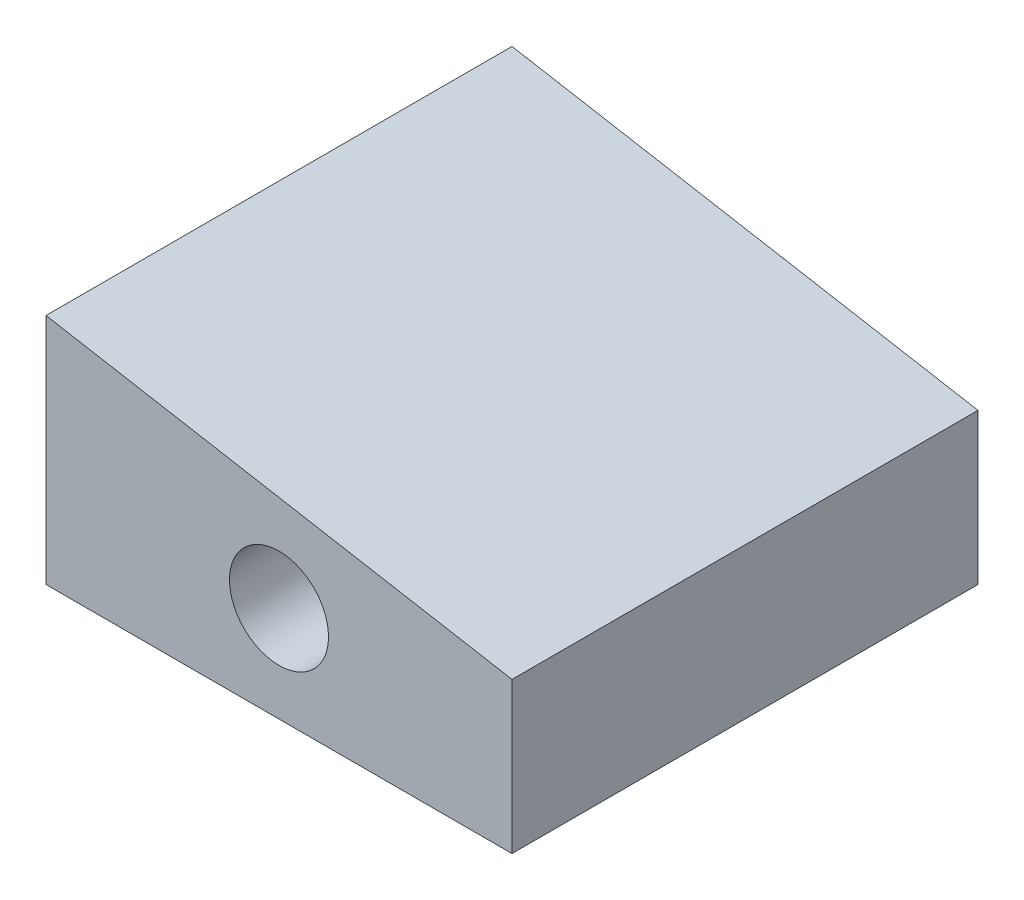
SolidWorks part; units mm, degrees
material "POM 乙缩醛共聚物"
ref_plane "前视基准面" through (0, 0, 0) normal (0, 0, 1) x (1, 0, 0)
ref_plane "上视基准面" through (0, 0, 0) normal (0, 1, 0) x (1, 0, 0)
ref_plane "右视基准面" through (0, 0, 0) normal (1, 0, 0) x (0, 0, -1)
sketch "草图1" plane through (0, 0, 0) normal (0, 0, 1) x (1, 0, 0)
  line L0 (0, 0) -> (0, 10)
  line L1 (0, 10) -> (20, 6.4735)
  line L2 (20, 6.4735) -> (20, 0)
  line L3 (20, 0) -> (0, 0)
  line L4 (10, 0) -> (10, 8.2367) construction
  circle A1 centre (10, 4.1184) radius 2.125
  point P6 (10, 4.1184)
  dimension "D3" = 4.25
  dimension "D1" = 10
  dimension "D2" = 20
  dimension "D6" = 10
extrude "凸台-拉伸1" add sketch "草图1" along normal blind 20
